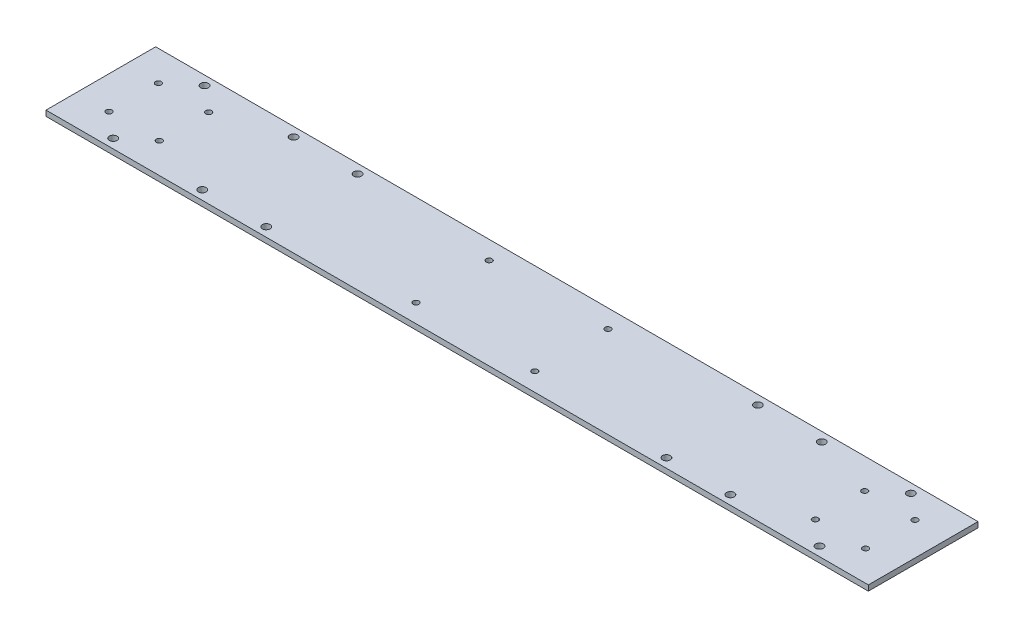
SolidWorks part; units mm, degrees
ref_plane "前视基准面" through (0, 0, 0) normal (0, 0, 1) x (1, 0, 0)
ref_plane "上视基准面" through (0, 0, 0) normal (0, 1, 0) x (1, 0, 0)
ref_plane "右视基准面" through (0, 0, 0) normal (1, 0, 0) x (0, 0, -1)
sketch "草图1" plane through (0, 0, 0) normal (0, 1, 0) x (1, 0, 0)
  line L0 (-21.4414, 42.5) -> (-21.4414, 102.5) construction
  line L1 (-246.4414, 42.5) -> (203.5586, 42.5)
  line L2 (-246.4414, 42.5) -> (-246.4414, 102.5)
  line L3 (-246.4414, 102.5) -> (203.5586, 102.5)
  line L4 (203.5586, 42.5) -> (203.5586, 102.5)
  line L5 (-61.4414, 102.5) -> (-61.4414, 168.5)
  line L6 (-61.4414, 168.5) -> (18.5586, 168.5)
  line L7 (18.5586, 168.5) -> (18.5586, 102.5)
  line L8 (-21.4414, 168.5) -> (-21.4414, 102.5) construction
  dimension "D1" = 450
  dimension "D2" = 60
  dimension "D3" = 66
  dimension "D4" = 80
extrude "凸台-拉伸1" add sketch "草图1" along normal blind 3 contours L1 L4 L3 L2
sketch "草图2" plane through (0, 3, 0) normal (0, 1, 0) x (1, 0, 0)
  line L0 (-228.4414, 59) -> (-228.4414, 86) construction
  line L1 (-200.9414, 59) -> (-200.9414, 86) construction
  line L2 (-228.4414, 86) -> (-200.9414, 86) construction
  line L3 (-130.9414, 47.5) -> (-130.9414, 97.5) construction
  line L4 (-214.6914, 86) -> (-214.6914, 102.5) construction
  line L5 (-214.6914, 97.5) -> (-165.9414, 97.5) construction
  line L6 (-246.4414, 72.5) -> (203.5586, 72.5) construction
  line L7 (-246.4414, 42.5) -> (-246.4414, 102.5) construction
  line L8 (203.5586, 42.5) -> (203.5586, 102.5) construction
  line L9 (-228.4414, 72.5) -> (-130.9414, 72.5) construction
  line L10 (-246.4414, 102.5) -> (203.5586, 102.5) construction
  line L11 (-21.4414, 102.5) -> (-21.4414, 42.5) construction
  line L12 (-246.4414, 42.5) -> (203.5586, 42.5) construction
  circle A0 centre (-228.4414, 86) radius 1.6
  circle A1 centre (-228.4414, 59) radius 1.6
  circle A2 centre (-200.9414, 86) radius 1.6
  circle A3 centre (-200.9414, 59) radius 1.6
  circle A4 centre (-130.9414, 97.5) radius 2.1
  circle A5 centre (-165.9414, 97.5) radius 2.1
  circle A6 centre (-130.9414, 47.5) radius 2.1
  circle A7 centre (-165.9414, 47.5) radius 2.1
  circle A8 centre (-214.6914, 97.5) radius 2.1
  circle A9 centre (-214.6914, 47.5) radius 2.1
  circle A10 centre (158.0586, 86) radius 1.6
  circle A11 centre (171.8086, 47.5) radius 2.1
  circle A12 centre (185.5586, 59) radius 1.6
  circle A13 centre (158.0586, 59) radius 1.6
  circle A14 centre (123.0586, 47.5) radius 2.1
  circle A15 centre (88.0586, 47.5) radius 2.1
  circle A16 centre (88.0586, 97.5) radius 2.1
  circle A17 centre (123.0586, 97.5) radius 2.1
  circle A18 centre (171.8086, 97.5) radius 2.1
  circle A19 centre (185.5586, 86) radius 1.6
  point P3 (-228.4414, 72.5)
  point P8 (-200.9414, 72.5)
  point P13 (-130.9414, 72.5)
  dimension "D2" = 3.2
  dimension "D5" = 5
  dimension "D6" = 70
  dimension "D1" = 27
  dimension "D3" = 18
  dimension "D4" = 45.5
extrude "切除-拉伸1" cut sketch "草图2" against normal through all
sketch "草图3" plane through (0, 3, 0) normal (0, 1, 0) x (1, 0, 0)
  line L0 (-21.4414, 102.5) -> (-21.4414, 42.5) construction
  line L1 (-246.4414, 102.5) -> (203.5586, 102.5) construction
  line L2 (-246.4414, 42.5) -> (203.5586, 42.5) construction
  line L3 (-56.7574, 72.5) -> (19.7761, 72.5) construction
  circle A0 centre (-53.9414, 92.5) radius 1.6
  circle A1 centre (11.0586, 92.5) radius 1.6
  circle A2 centre (11.0586, 52.5) radius 1.6
  circle A3 centre (-53.9414, 52.5) radius 1.6
  dimension "D1" = 3.2
  dimension "D2" = 32.5
  dimension "D3" = 20
  dimension "D4" = 40
  dimension "D5" = 10
extrude "铰链孔" cut sketch "草图3" against normal blind 10
